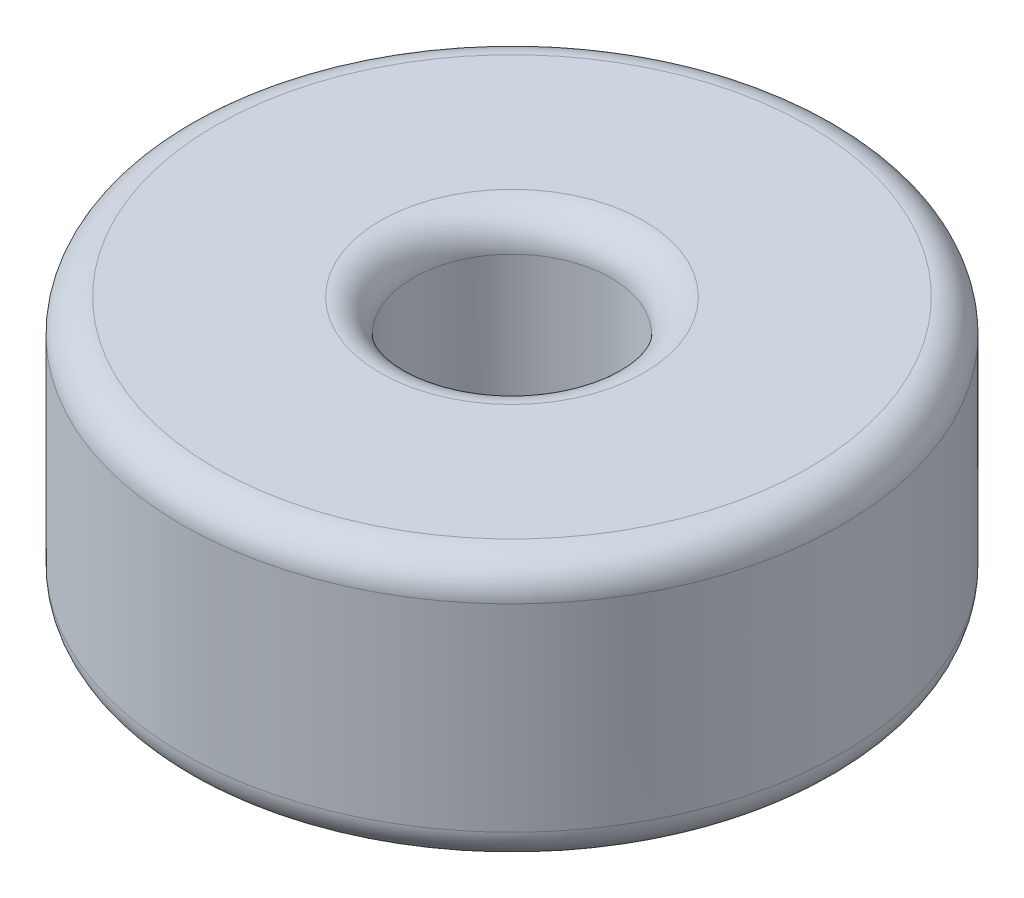
SolidWorks part; units mm, degrees
ref_plane "Plan de face" through (0, 0, 0) normal (0, 0, 1) x (1, 0, 0)
ref_plane "Plan de dessus" through (0, 0, 0) normal (0, 1, 0) x (1, 0, 0)
ref_plane "Plan de droite" through (0, 0, 0) normal (1, 0, 0) x (0, 0, -1)
sketch "Esquisse1" plane through (0, 0, 0) normal (0, 0, 1) x (1, 0, 0)
  line L0 (0, 0) -> (0, 4.3533) construction
  line L2 (1.5, 0) -> (5, 0)
  line L3 (1.5, 0) -> (1.5, 4)
  line L4 (1.5, 4) -> (5, 4)
  line L5 (5, 0) -> (5, 4)
  dimension "D1" = 3
  dimension "D2" = 10
  dimension "D3" = 4
revolve "Révolution1" add sketch "Esquisse1" angle 360 about L0
fillet "Congé1" radius 0.5 4 edges at (0, 0, -1.5) (0, 0, -5) (0, 4, -5) (0, 4, -1.5)
